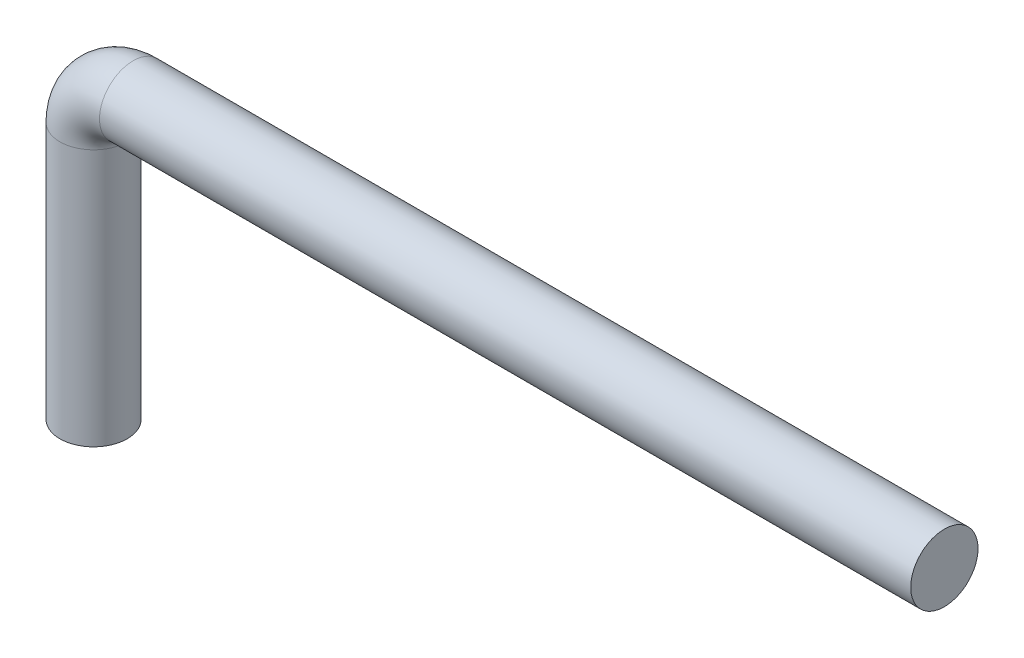
SolidWorks part; units mm, degrees
ref_plane "Front Plane" through (0, 0, 0) normal (0, 0, 1) x (1, 0, 0)
ref_plane "Top Plane" through (0, 0, 0) normal (0, 1, 0) x (1, 0, 0)
ref_plane "Right Plane" through (0, 0, 0) normal (1, 0, 0) x (0, 0, -1)
sketch "Sketch2" plane through (0, 0, 0) normal (0, 0, 1) x (1, 0, 0)
  line L0 (0, 0) -> (-260.35, 0)
  line L1 (-273.05, -12.7) -> (-273.05, -95.25)
  arc A0 (-260.35, 0) -> (-273.05, -12.7) centre (-260.35, -12.7) ccw
  point P6 (-273.05, 0)
  dimension "D3" = 12.7
  dimension "D1" = 273.05
  dimension "D2" = 95.25
sketch "Sketch3" plane through (0, 0, 0) normal (1, 0, 0) x (0, 0, -1)
  circle A0 centre (0, 0) radius 10.795
  dimension "D1" = 21.59
sweep "Sweep1" add profiles "Sketch3" path "Sketch2"
